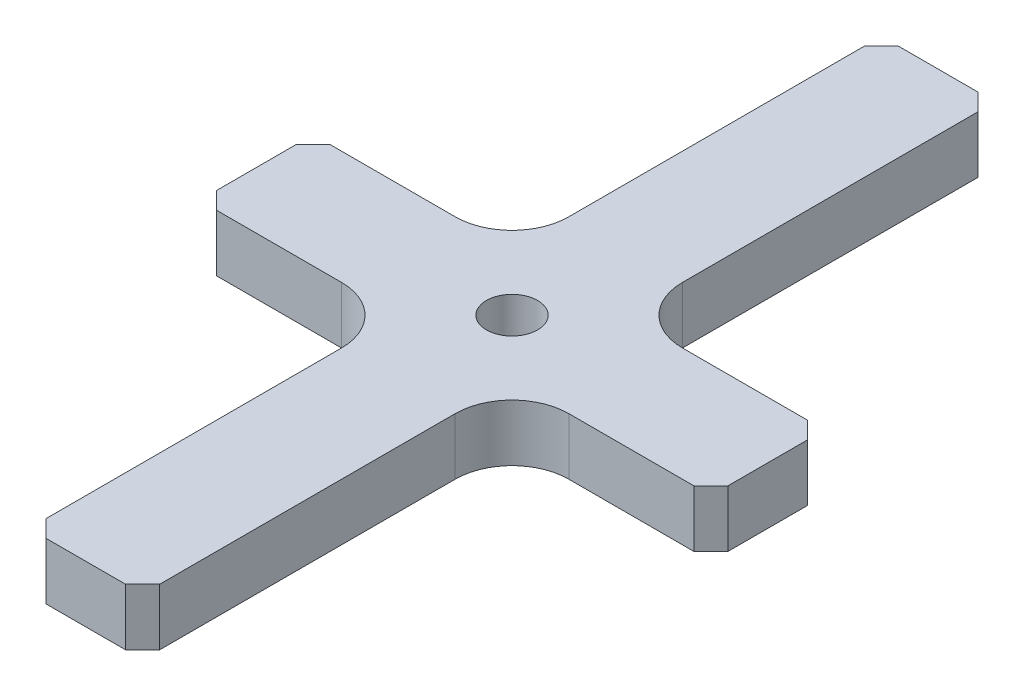
SolidWorks part; units mm, degrees
material "Thornel Mat VMA"
ref_plane "Front Plane" through (0, 0, 0) normal (0, 0, 1) x (1, 0, 0)
ref_plane "Top Plane" through (0, 0, 0) normal (0, 1, 0) x (1, 0, 0)
ref_plane "Right Plane" through (0, 0, 0) normal (1, 0, 0) x (0, 0, -1)
sketch "Sketch2" plane through (0, 0, 0) normal (0, 1, 0) x (1, 0, 0)
  line L0 (0, 0) -> (0, 37.5) construction
  line L1 (-5, 37.5) -> (5, 37.5)
  line L2 (5, 37.5) -> (5, 5)
  line L4 (22.5, 5) -> (5, 5)
  line L5 (22.5, -5) -> (22.5, 5)
  line L6 (-22.5, -5) -> (-22.5, 5)
  line L7 (-22.5, 5) -> (-5, 5)
  line L8 (-5, 37.5) -> (-5, 5)
  line L9 (0, 0) -> (-22.5, 0) construction
  line L10 (22.5, -5) -> (5, -5)
  line L11 (5, -37.5) -> (5, -5)
  line L12 (-5, -37.5) -> (5, -37.5)
  line L13 (-5, -37.5) -> (-5, -5)
  line L14 (-22.5, -5) -> (-5, -5)
  point P12 (22.5, 0)
  point P17 (7.9504, -35)
  dimension "D1" = 5
  dimension "D2" = 37.5
  dimension "D3" = 22.5
  dimension "D4" = 10
extrude "Boss-Extrude1" add sketch "Sketch2" along normal mid plane 5
fillet "Fillet1" radius 5 4 edges at (-5, 0, -5) (5, 0, -5) (5, 0, 5) (-5, 0, 5)
chamfer "Chamfer1" distance 1.5 angle 45 8 edges at (-22.5, 0, 5) (-22.5, 0, -5) (-5, 0, -37.5) (5, 0, -37.5) (22.5, 0, -5) (22.5, 0, 5) (5, 0, 37.5) (-5, 0, 37.5)
hole_wizard "M4 Clearance Hole1" positions "Sketch3" profile "Sketch4" hole size "M4" standard "ANSI Metric"
sketch "Sketch3" plane through (0, 2.5, 0) normal (0, 1, 0) x (1, 0, 0)
  point P0 (0, 0)
sketch "Sketch4" plane through (0, 2.5, 0) normal (1, 0, 0) x (0, 0, 1)
  line L0 (0, 0) -> (0, 6.5519)
  line L1 (0, 6.5519) -> (2.25, 5.2)
  line L2 (2.25, 5.2) -> (2.25, 0)
  line L5 (2.25, 0) -> (0, 0)
  line L10 (0, 6.5519) -> (-2.25, 5.2) construction
  line L11 (0, -6.35) -> (0, 107.95) construction
  dimension "Hole Dia." = 4.5
  dimension "Hole Depth" = 5.2
  dimension "Drill Angle" = 118
